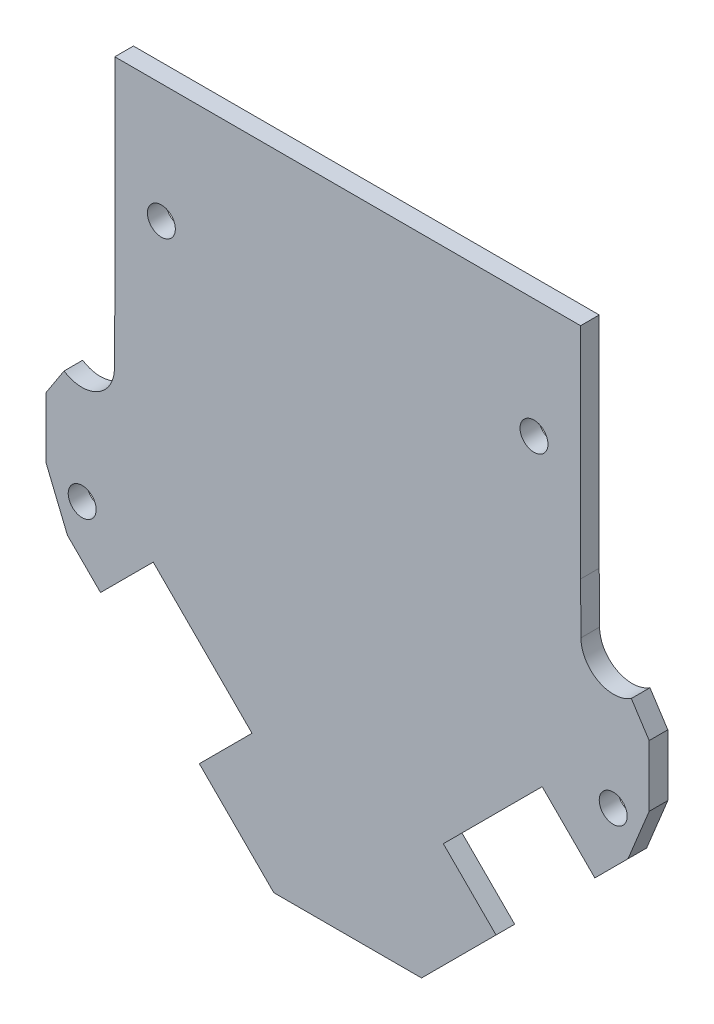
SolidWorks part; units mm, degrees
ref_plane "Front" through (0, 0, 0) normal (0, 0, 1) x (1, 0, 0)
ref_plane "Top" through (0, 0, 0) normal (0, 1, 0) x (1, 0, 0)
ref_plane "Right" through (0, 0, 0) normal (1, 0, 0) x (0, 0, -1)
sketch "Sketch1" plane through (0, 0, 0) normal (0, 0, 1) x (1, 0, 0)
  line L0 (-15, 13.5) -> (-15, 38.5)
  line L1 (15, 13.5) -> (26.8117, -4.6883)
  line L2 (15, -26.5) -> (7.9289, -33.5711)
  line L3 (7.9289, -33.5711) -> (7.9289, -52.5711)
  line L4 (-15, 13.5) -> (-26.8117, -4.6883)
  line L5 (-15, -26.5) -> (-7.9289, -33.5711)
  line L6 (-7.9289, -33.5711) -> (-7.9289, -52.5711)
  line L7 (-7.9289, -52.5711) -> (7.9289, -52.5711)
  line L8 (26.8117, -4.6883) -> (15, -16.5)
  line L9 (15, -16.5) -> (15, -26.5)
  line L10 (-26.8117, -4.6883) -> (-15, -16.5)
  line L11 (-15, -16.5) -> (-15, -26.5)
  line L12 (-15, 38.5) -> (15, 38.5)
  line L13 (15, 38.5) -> (15, 13.5)
  dimension "D1" = 30
  dimension "D2" = 40
  dimension "D3" = 40
  dimension "D4" = 10
  dimension "D5" = 10
  dimension "D6" = 19
  dimension "D7" = 327
  dimension "D8" = 25
  dimension "D9" = 15
  dimension "D10" = 15
  dimension "D11" = 10
  dimension "D12" = 135
  dimension "D13" = 135
  dimension "D14" = 327
  dimension "D15" = 135
  dimension "D16" = 135
extrude "Extrude1" add sketch "Sketch1" along normal blind 2
sketch "Sketch4" plane through (0, 0, 2) normal (0, 0, 1) x (1, 0, 0)
  line L0 (-26.8117, -4.6883) -> (-32.3637, -6.9632)
  line L1 (-32.3637, -6.9632) -> (-30.0888, -12.5152)
  line L2 (-30.0888, -12.5152) -> (-22.2121, -9.2879)
  line L3 (-26.8117, -4.6883) -> (-15, -16.5) construction
  line L4 (-22.2121, -9.2879) -> (-26.8117, -4.6883)
  circle A0 centre (-28.5, -8.6) radius 1.5
  dimension "D3" = 3
  dimension "D1" = 6
  dimension "D2" = 6
  dimension "D4" = 28.5
  dimension "D5" = 8.6
extrude "Extrude3" add sketch "Sketch4" against normal up to surface (2 mm away) up to face at (0, -11.6901, 0)
mirror "Mirror1" about plane through (0, 0, 0) normal (1, 0, 0) of "Extrude3"
sketch "Sketch6" plane through (0, 0, 2) normal (0, 0, 1) x (1, 0, 0)
  line L0 (0, -44.5711) -> (-7.9289, -44.5711)
  line L1 (-7.9289, -33.5711) -> (-7.9289, -52.5711) construction
  line L2 (-7.9289, -44.5711) -> (-18, -54.6421)
  line L3 (-18, -54.6421) -> (18, -54.6421)
  line L4 (18, -54.6421) -> (7.9289, -44.5711)
  line L5 (7.9289, -44.5711) -> (0, -44.5711)
  line L6 (7.9289, -52.5711) -> (7.9289, -33.5711) construction
  line L7 (-7.9289, -52.5711) -> (7.9289, -52.5711) construction
  dimension "D1" = 45
  dimension "D2" = 36
  dimension "D3" = 8
extrude "Extrude5" add sketch "Sketch6" against normal up to surface (2 mm away) up to face at (0, -11.0597, 0)
fillet "Fillet2" radius 3 2 edges at (18, -54.6421, 1) (-18, -54.6421, 1)
sketch "Sketch7" plane through (0, 0, 2) normal (0, 0, 1) x (1, 0, 0)
  line L0 (-10.7574, -54.6421) -> (10.7574, -54.6421) construction
  circle A0 centre (-11, -52.0021) radius 1.5
  dimension "D3" = 3
  dimension "D1" = 2.64
  dimension "D2" = 11
extrude "Extrude6" cut sketch "Sketch7" against normal up to surface (2 mm away) up to face at (0, -17.289, 0)
mirror "Mirror4" about plane through (0, 0, 0) normal (1, 0, 0) of "Extrude6"
sketch "Sketch8" plane through (0, 0, 2) normal (0, 0, 1) x (1, 0, 0)
  line L0 (-26.8117, -4.6883) -> (-32.3637, -6.9632)
  line L1 (-26.8117, -4.6883) -> (-15, 13.5)
  line L2 (-15, 26.3525) -> (-15, 13.5)
  line L3 (-15, 26.3525) -> (-32.3637, -0.3852)
  line L4 (-32.3637, -0.3852) -> (-32.3637, -6.9632)
  dimension "D1" = 7
extrude "Extrude7" add sketch "Sketch8" against normal up to surface (2 mm away) up to face at (30, -8.6, 0)
sketch "Sketch9" plane through (0, 0, 2) normal (0, 0, 1) x (1, 0, 0)
  line L0 (-22.2121, -9.2879) -> (-25.2217, -10.521)
  line L1 (-30.0888, -12.5152) -> (-22.2121, -9.2879) construction
  line L2 (-25.2217, -10.521) -> (-15, -20.7426)
  line L3 (-15, -16.5) -> (-15, -26.5) construction
  line L4 (-15, -20.7426) -> (-15, -16.5)
  line L5 (-15, -16.5) -> (-22.2121, -9.2879)
  dimension "D1" = 3
extrude "Extrude8" add sketch "Sketch9" against normal up to surface (2 mm away) up to face at (30, -8.6, 0)
sketch "Sketch10" plane through (0, 0, 2) normal (0, 0, 1) x (1, 0, 0)
  line L0 (-25.2217, -10.521) -> (-30.0888, -12.5152)
  line L1 (-30.0888, -12.5152) -> (-23.7026, -18.9014)
  line L2 (-23.7026, -18.9014) -> (-20.2719, -15.4707)
  line L3 (-25.2217, -10.521) -> (-15, -20.7426) construction
  line L4 (-25.2217, -10.521) -> (-20.2719, -15.4707)
  dimension "D1" = 7
extrude "Extrude9" add sketch "Sketch10" against normal up to surface (2 mm away) up to face at (-0.3567, -16.8024, 0)
sketch "Sketch11" plane through (0, 0, 2) normal (0, 0, 1) x (1, 0, 0)
  line L0 (-15.3222, -20.4205) -> (-18.7529, -23.8512)
  line L1 (-20.2719, -15.4707) -> (-15, -20.7426) construction
  line L2 (-18.7529, -23.8512) -> (-7.9289, -34.6751)
  line L3 (-30.0888, -12.5152) -> (-23.7026, -18.9014) construction
  line L4 (-15, -26.5) -> (-15, -20.7426)
  line L5 (-15, -20.7426) -> (-15.3222, -20.4205)
  line L6 (-23.7026, -18.9014) -> (-20.2719, -15.4707) construction
  line L8 (-7.9289, -33.5711) -> (-7.9289, -44.5711) construction
  line L9 (-7.9289, -34.6751) -> (-7.9289, -33.5711)
  line L10 (-7.9289, -33.5711) -> (-15, -26.5)
  dimension "D1" = 7
extrude "Extrude10" add sketch "Sketch11" against normal up to surface (2 mm away) up to face at (-1.0926, -17.0843, 0)
sketch "Sketch12" plane through (0, 0, 2) normal (0, 0, 1) x (1, 0, 0)
  line L0 (-25, 10.9539) -> (-25, 38.5)
  line L1 (-15, 26.3525) -> (-32.3637, -0.3852) construction
  line L2 (-25, 38.5) -> (-15, 38.5)
  line L3 (-15, 38.5) -> (-15, 26.3525)
  line L4 (-15, 26.3525) -> (-25, 10.9539)
  dimension "D1" = 10
extrude "Extrude11" add sketch "Sketch12" against normal up to surface (2 mm away) up to face at (-1.2556, -17.0096, 0)
mirror "Mirror5" about plane through (0, 0, 0) normal (1, 0, 0) of "Extrude9", "Extrude7", "Extrude8", "Extrude10"
mirror "Mirror6" about plane through (0, 0, 0) normal (1, 0, 0) of "Extrude11"
sketch "Sketch13" plane through (0, 0, 0) normal (0, 0, -1) x (-1, 0, 0)
  line L1 (-25.1343, -34.6751) -> (27.3105, -34.6751)
  line L2 (-25.1343, -34.6751) -> (-25.1343, -59.1014)
  line L3 (-25.1343, -59.1014) -> (27.3105, -59.1014)
  line L4 (27.3105, -34.6751) -> (27.3105, -59.1014)
extrude "Extrude12" cut sketch "Sketch13" against normal up to surface (2 mm away) up to face at (0, -17.9363, 2)
sketch "Sketch14" plane through (0, 0, 2) normal (0, 0, 1) x (1, 0, 0)
  circle A0 centre (-20, 21.73) radius 1.5
  circle A1 centre (-28.5, -8.6) radius 1.5 construction
  circle A2 centre (20, 21.73) radius 1.5
  circle A3 centre (28.5, -8.6) radius 1.5 construction
  dimension "D1" = 8.5
  dimension "D2" = 30.33
  dimension "D3" = 3
  dimension "D4" = 3
  dimension "D5" = 8.5
extrude "Extrude13" cut sketch "Sketch14" against normal up to surface (2 mm away) up to face at (0, -8.3729, 0)
sketch "Sketch15" plane through (0, 0, 0) normal (0, 0, -1) x (-1, 0, 0)
  line L0 (26.531, -16.073) -> (20.8742, -10.4162)
  line L1 (23.7026, -18.9014) -> (30.0888, -12.5152) construction
  line L2 (20.8742, -10.4162) -> (10.2676, -21.0228)
  line L3 (10.2676, -21.0228) -> (15.9244, -26.6796)
  line L4 (7.9289, -34.6751) -> (18.7529, -23.8512) construction
  line L5 (15.9244, -26.6796) -> (26.531, -16.073)
  line L6 (20.2719, -15.4707) -> (23.7026, -18.9014) construction
  line L7 (18.7529, -23.8512) -> (15.3222, -20.4205) construction
  line L8 (-26.531, -16.073) -> (-20.8742, -10.4162)
  line L9 (-23.7026, -18.9014) -> (-30.0888, -12.5152) construction
  line L10 (-20.8742, -10.4162) -> (-10.2676, -21.0228)
  line L11 (-10.2676, -21.0228) -> (-15.9244, -26.6796)
  line L12 (-7.9289, -34.6751) -> (-18.7529, -23.8512) construction
  line L13 (-15.9244, -26.6796) -> (-26.531, -16.073)
  line L14 (-20.2719, -15.4707) -> (-23.7026, -18.9014) construction
  line L15 (-18.7529, -23.8512) -> (-15.3222, -20.4205) construction
  dimension "D1" = 4
  dimension "D2" = 4
  dimension "D3" = 8
  dimension "D4" = 4
  dimension "D5" = 4
  dimension "D6" = 8
extrude "Extrude14" cut sketch "Sketch15" against normal up to surface (2 mm away) up to face at (21.5, 21.73, 2)
sketch "Sketch16" plane through (0, 0, 0) normal (0, 0, -1) x (-1, 0, 0)
  line L0 (-25, 10.9539) -> (-25.0402, 5.5025)
  line L1 (-32.3637, -0.3852) -> (-25, 10.9539) construction
  line L2 (-25, 10.9539) -> (-30.4464, 2.5672)
  line L3 (25, 10.9539) -> (25.0402, 5.5025)
  line L4 (25, 10.9539) -> (30.4464, 2.5672)
  line L6 (32.3637, -0.3852) -> (25, 10.9539) construction
  arc A0 (25.0402, 5.5025) -> (30.4464, 2.5672) centre (28.5402, 5.5025) ccw
  arc A1 (-30.4464, 2.5672) -> (-25.0402, 5.5025) centre (-28.5402, 5.5025) ccw
  dimension "D3" = 3.5
extrude "Extrude15" cut sketch "Sketch16" against normal up to surface (2 mm away) up to face at (0, -7.9276, 2)
sketch "Sketch17" plane through (0, 0, 0) normal (0, 0, -1) x (-1, 0, 0)
  line L0 (-25, 38.5) -> (-25, 10.9539) construction
  line L1 (25, 38.5) -> (-25, 38.5)
  line L2 (25, 38.5) -> (25, 34.5)
  line L3 (25, 34.5) -> (-25, 34.5)
  line L4 (-25, 38.5) -> (-25, 34.5)
  dimension "D1" = 4
extrude "Extrude17" cut sketch "Sketch17" against normal up to surface (2 mm away) up to face at (0, -6.0679, 2)
